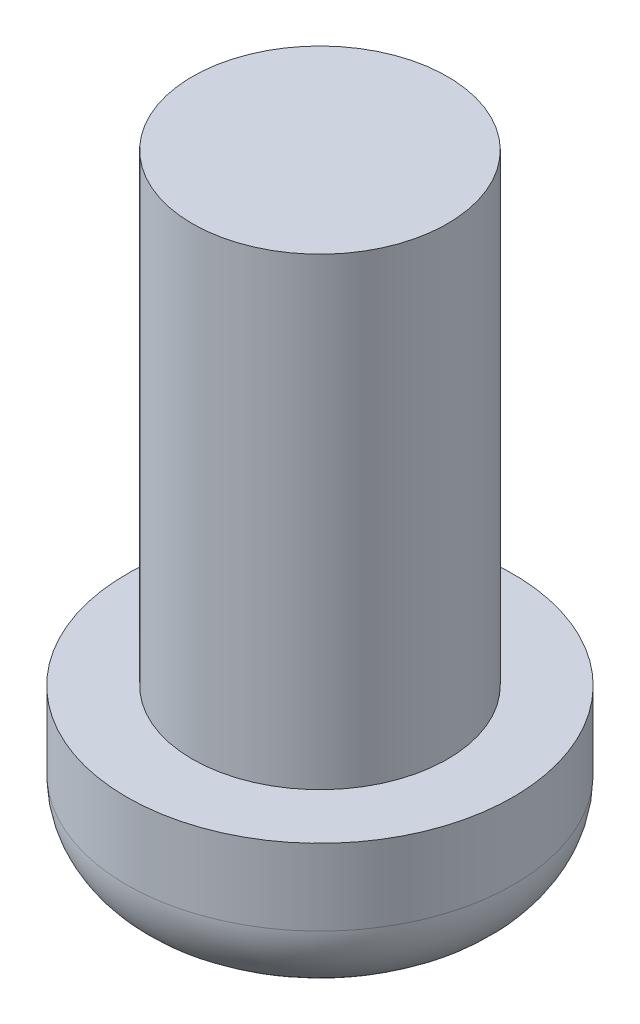
SolidWorks part; units mm, degrees
ref_plane "Front Plane" through (0, 0, 0) normal (0, 0, 1) x (1, 0, 0)
ref_plane "Top Plane" through (0, 0, 0) normal (0, 1, 0) x (1, 0, 0)
ref_plane "Right Plane" through (0, 0, 0) normal (1, 0, 0) x (0, 0, -1)
sketch "Sketch1" plane through (0, 0, 0) normal (0, 1, 0) x (1, 0, 0)
  circle A1 centre (0, 0) radius 2.5
  dimension "D1" = 5
extrude "Boss-Extrude1" add sketch "Sketch1" along normal blind 2
sketch "Sketch2" plane through (0, 2, 0) normal (0, 1, 0) x (1, 0, 0)
  circle A0 centre (0, 0) radius 1.65
  dimension "D1" = 3.3
extrude "Boss-Extrude2" add sketch "Sketch2" along normal blind 6
fillet "Fillet1" radius 1.016 1 edges at (0, 0, 2.5)
